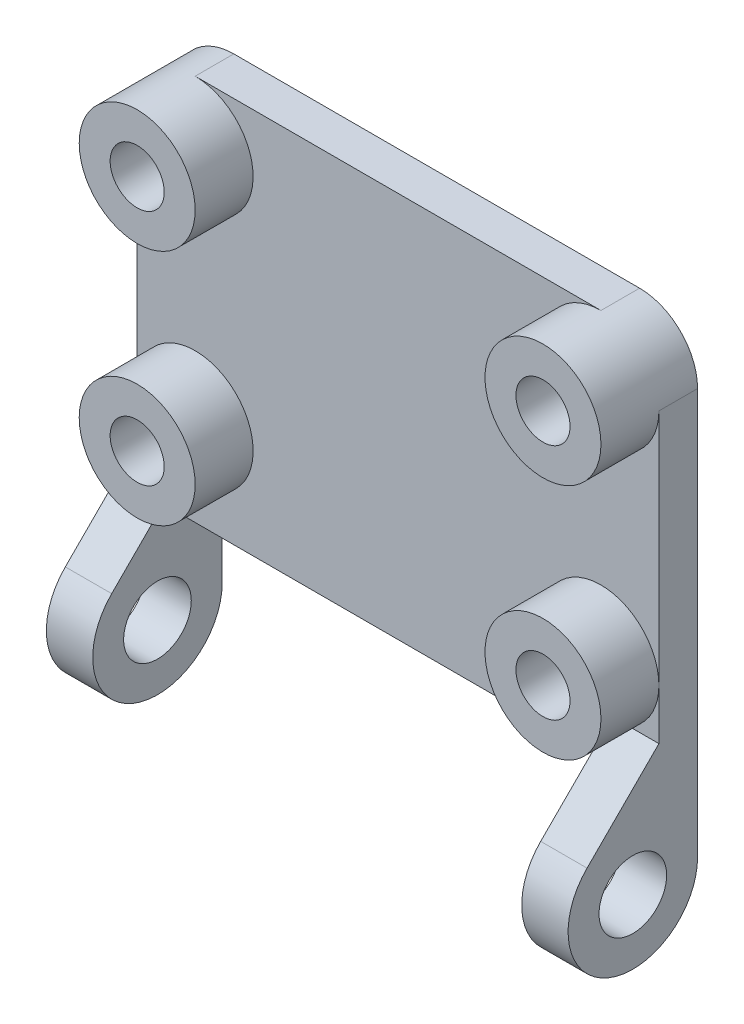
SolidWorks part; units mm, degrees
material "S235JR"
ref_plane "Piano X" through (0, 0, 0) normal (0, 0, 1) x (1, 0, 0)
ref_plane "Piano Y" through (0, 0, 0) normal (0, 1, 0) x (1, 0, 0)
ref_plane "Piano Z" through (0, 0, 0) normal (1, 0, 0) x (0, 0, -1)
sketch "Schizzo1" plane through (0, 0, 0) normal (0, 0, 1) x (1, 0, 0)
  line L1 (-13.5, -10) -> (13.5, -10)
  line L2 (-13.5, -10) -> (-13.5, 10)
  line L3 (-13.5, 10) -> (13.5, 10)
  line L4 (13.5, -10) -> (13.5, 10)
  line L5 (0, 10) -> (0, -10) construction
  line L6 (-13.5, 0) -> (13.5, 0) construction
  line L15 (10.5, -5.3) -> (-10.5, -5.3) construction
  line L16 (10.5, -5.3) -> (10.5, 7) construction
  line L17 (10.5, 7) -> (-10.5, 7) construction
  line L18 (-10.5, -5.3) -> (-10.5, 7) construction
  line L19 (0, 7) -> (0, -5.3) construction
  line L20 (10.5, 0.85) -> (-10.5, 0.85) construction
  circle A0 centre (-10.5, 7) radius 1.4
  circle A1 centre (-10.5, -5.3) radius 1.4
  circle A2 centre (10.5, -5.3) radius 1.4
  circle A3 centre (10.5, 7) radius 1.4
  point P0 (0, 0)
  point P2 (0, 0.85)
  dimension "D3" = 2.8
  dimension "D1" = 27
  dimension "D2" = 20
  dimension "D4" = 12.3
  dimension "D5" = 21
  dimension "D6" = 3
extrude "Estrusione-Estrusione1" add sketch "Schizzo1" along normal blind 2
fillet "Raccordo1" radius 3 2 edges at (13.5, 10, 1) (-13.5, 10, 1)
sketch "Schizzo2" plane through (13.5, 0, 0) normal (1, 0, 0) x (0, 0, -1)
  line L0 (0, -10) -> (0, -14)
  line L1 (0, -10) -> (-2, -10)
  line L2 (-5.7188, -11.6312) -> (-2, -7.9124)
  line L3 (-2, -10) -> (-2, 7) construction
  line L4 (-2, -7.9124) -> (-2, -10)
  arc A0 (-5.7188, -11.6312) -> (0, -14) centre (-3.35, -14) ccw
  circle A1 centre (-3.35, -14) radius 1.75
  point P1 (0, 0)
  point P12 (-3.35, -13.35)
  point P13 (-3.35, -14.2567)
  dimension "D1" = 1.6
  dimension "D2" = 3.5
  dimension "D3" = 4
  dimension "D4" = 45
extrude "Estrusione-Estrusione2" add sketch "Schizzo2" against normal blind 2.4
mirror "Specchia1" about plane through (0, 0, 0) normal (1, 0, 0) of "Estrusione-Estrusione2"
sketch "Schizzo3" plane through (0, 0, 2) normal (0, 0, 1) x (1, 0, 0)
  circle A0 centre (-10.5, 7) radius 3
  circle A1 centre (-10.5, -5.3) radius 3
  circle A2 centre (10.5, -5.3) radius 3
  circle A3 centre (10.5, 7) radius 3
  circle A4 centre (10.5, 7) radius 1.4 construction
  circle A5 centre (10.5, -5.3) radius 1.4 construction
  circle A6 centre (-10.5, -5.3) radius 1.4 construction
  circle A7 centre (-10.5, 7) radius 1.4 construction
  circle A8 centre (10.5, 7) radius 1.4
  circle A9 centre (10.5, -5.3) radius 1.4
  circle A10 centre (-10.5, -5.3) radius 1.4
  circle A11 centre (-10.5, 7) radius 1.4
  dimension "D1" = 1.6
extrude "Estrusione-Estrusione3" add sketch "Schizzo3" along normal blind 3
equation "\"D1@Schizzo3\"=0.4*4"
equation "\"D1@Schizzo2\"=0.4*4"
